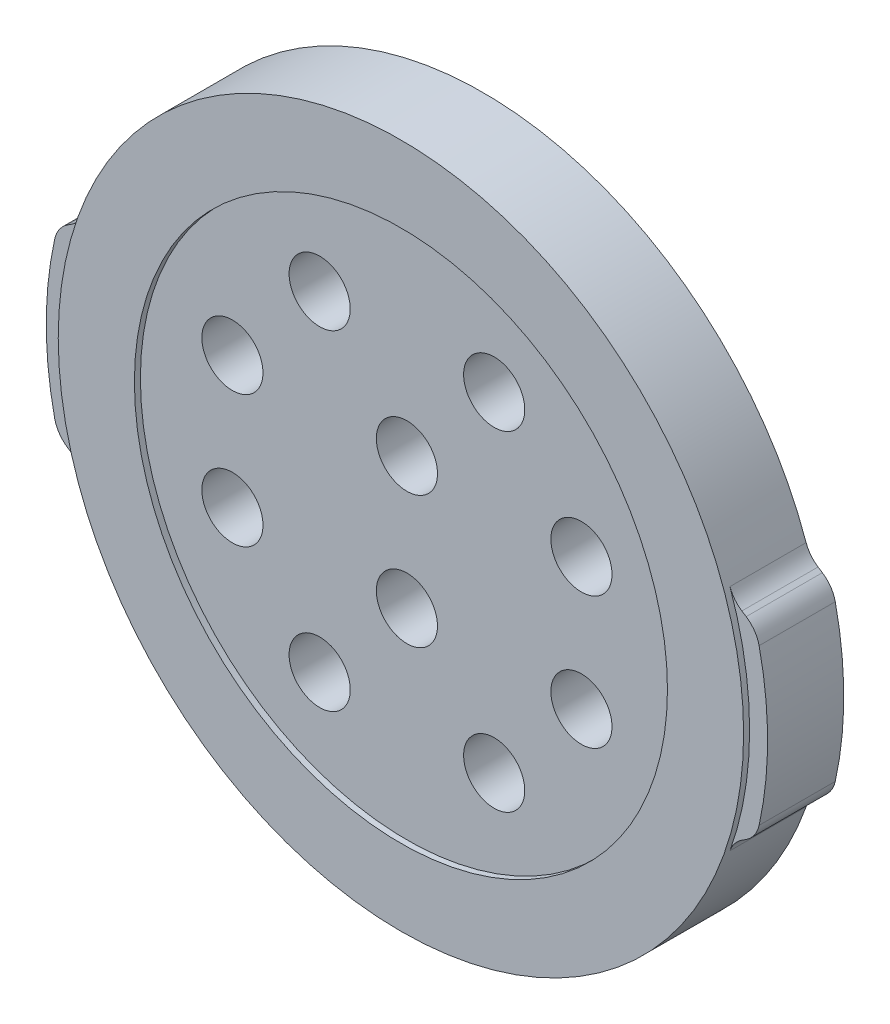
SolidWorks part; units mm, degrees
material "Acrylic (Medium-high impact)"
ref_plane "Front Plane" through (0, 0, 0) normal (0, 0, 1) x (1, 0, 0)
ref_plane "Top Plane" through (0, 0, 0) normal (0, 1, 0) x (1, 0, 0)
ref_plane "Right Plane" through (0, 0, 0) normal (1, 0, 0) x (0, 0, -1)
sketch "Sketch1" plane through (0, 0, 0) normal (0, 0, 1) x (1, 0, 0)
  line L0 (54.4047, 17.5) -> (58.2497, 15)
  line L1 (54.4047, -17.5) -> (58.2497, -15)
  line L2 (-54.4047, 17.5) -> (-58.2497, 15)
  line L3 (-54.4047, -17.5) -> (-58.2497, -15)
  line L4 (0, 53.975) -> (0, 0) construction
  line L5 (0, 0) -> (-46.7437, 26.9875) construction
  line L6 (-46.7437, 26.9875) -> (-49.4934, 28.575) construction
  arc A0 (54.4047, 17.5) -> (-54.4047, 17.5) centre (0, 0) ccw
  circle A1 centre (0, 53.975) radius 1.6
  circle A2 centre (46.7437, 26.9875) radius 1.6
  circle A3 centre (46.7437, -26.9875) radius 1.6
  circle A4 centre (0, -53.975) radius 1.6
  circle A5 centre (-46.7437, -26.9875) radius 1.6
  circle A6 centre (-46.7437, 26.9875) radius 1.6
  arc A7 (58.2497, -15) -> (58.2497, 15) centre (0, 0) ccw
  arc A8 (-58.2497, 15) -> (-58.2497, -15) centre (0, 0) ccw
  arc A9 (-54.4047, -17.5) -> (54.4047, -17.5) centre (0, 0) ccw
  point P17 (0, 0)
  point P26 (-60.15, 0)
  point P27 (60.15, 0)
  dimension "D1" = 114.3
  dimension "D2" = 3.175
  dimension "D3" = 3.2
  dimension "D7" = 3
  dimension "D5" = 35
  dimension "D6" = 30
  dimension "D8" = 60
  dimension "D9" = 3.175
  dimension "D4" = 6
extrude "Boss-Extrude1" add sketch "Sketch1" along normal blind 12.7
sketch "Sketch6" plane through (0, 0, 0) normal (0, 0, -1) x (-1, 0, 0)
  line L0 (0, 0) -> (0, 11) construction
  line L1 (0, 0) -> (0, -11) construction
  line L2 (-29.1033, 11) -> (0, 11) construction
  line L3 (0, 11) -> (29.1033, 11) construction
  line L4 (-29.1033, -11) -> (0, -11) construction
  line L5 (0, -11) -> (29.1033, -11) construction
  line L6 (-14.5516, -11) -> (-14.5516, -27.5) construction
  line L7 (14.5516, -11) -> (14.5516, -27.5) construction
  line L8 (-14.5516, 27.5) -> (-14.5516, 11) construction
  line L9 (14.5516, 27.5) -> (14.5516, 11) construction
  line L10 (-29.1033, -11) -> (0, 0) construction
  line L11 (0, 0) -> (-14.5516, -27.5) construction
  line L12 (29.1033, 11) -> (29.1033, -11) construction
  line L13 (29.1033, 11) -> (14.5516, 27.5) construction
  circle A0 centre (14.5516, 27.5) radius 5.1
  circle A1 centre (-29.1033, 11) radius 5.1
  circle A2 centre (-29.1033, -11) radius 5.1
  circle A3 centre (29.1033, -11) radius 5.1
  circle A4 centre (29.1033, 11) radius 5.1
  circle A5 centre (-14.5516, 27.5) radius 5.1
  circle A6 centre (0, -11) radius 5.1
  circle A7 centre (-14.5516, -27.5) radius 5.1
  circle A8 centre (0, 11) radius 5.1
  circle A9 centre (0, 0) radius 44.45 construction
  circle A10 centre (-14.5516, 27.5) radius 9 construction
  circle A11 centre (29.1033, 11) radius 9 construction
  circle A12 centre (29.1033, -11) radius 9 construction
  circle A13 centre (14.5516, 27.5) radius 9 construction
  circle A14 centre (-29.1033, 11) radius 9 construction
  circle A15 centre (-29.1033, -11) radius 9 construction
  circle A16 centre (0, 11) radius 9 construction
  circle A17 centre (-14.5516, -27.5) radius 9 construction
  circle A18 centre (0, -11) radius 9 construction
  circle A19 centre (14.5516, -27.5) radius 5.1
  circle A20 centre (14.5516, -27.5) radius 9 construction
  dimension "D1" = 10.2
  dimension "D2" = 88.9
  dimension "D3" = 22
  dimension "D6" = 18
extrude "Cut-Extrude2" cut sketch "Sketch6" against normal through all
fillet "Fillet1" radius 5 8 edges at (58.2497, -15, 6.35) (54.4047, -17.5, 6.35) (58.2497, 15, 6.35) (54.4047, 17.5, 6.35) (-54.4047, -17.5, 6.35) (-58.2497, -15, 6.35) (-58.2497, 15, 6.35) (-54.4047, 17.5, 6.35)
sketch "Sketch7" plane through (0, 0, 12.7) normal (0, 0, 1) x (1, 0, 0)
  circle A0 centre (0, 0) radius 57.15
  circle A1 centre (0, 0) radius 44.45
  arc A2 (53.8721, 19.0768) -> (-53.8721, 19.0768) centre (0, 0) ccw construction
  dimension "D1" = 88.9
extrude "ANALYSIS-SUPPORT" add sketch "Sketch7" along normal blind 1
sketch "Sketch8" plane through (0, 0, 0) normal (0, 0, -1) x (-1, 0, 0)
  circle A0 centre (0, 53.975) radius 2.75
  circle A1 centre (-46.7437, 26.9875) radius 2.75
  circle A2 centre (-46.7437, -26.9875) radius 2.75
  circle A3 centre (0, -53.975) radius 2.75
  circle A4 centre (46.7437, -26.9875) radius 2.75
  circle A5 centre (46.7437, 26.9875) radius 2.75
  dimension "D1" = 5.5
extrude "ANALYSIS-SCREW-HEAD" [suppressed] add sketch "Sketch8" along normal blind 1
